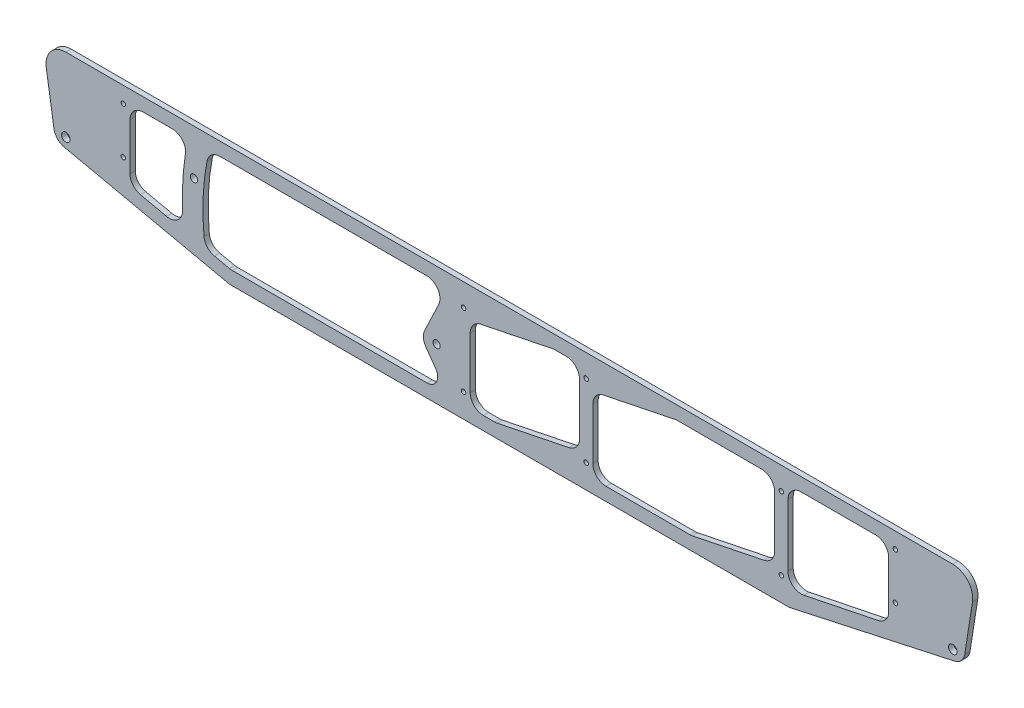
SolidWorks part; units mm, degrees
material "Сплав 2024"
ref_plane "Спереди" through (0, 0, 0) normal (0, 0, 1) x (1, 0, 0)
ref_plane "Сверху" through (0, 0, 0) normal (0, 1, 0) x (1, 0, 0)
ref_plane "Справа" through (0, 0, 0) normal (1, 0, 0) x (0, 0, -1)
sketch "Эскиз1" plane through (0, 0, 0) normal (0, 0, 1) x (1, 0, 0)
  line L0 (-349.8183, 27.6724) -> (-342.9109, -16.3036)
  line L1 (-350, 45) -> (350, 45) construction
  line L2 (-350, 45) -> (-350, -45) construction
  line L3 (-350, -45) -> (350, -45) construction
  line L4 (350, 45) -> (350, -45) construction
  line L5 (-350, 45) -> (350, -45) construction
  line L6 (-350, -45) -> (350, 45) construction
  line L7 (-342.9109, -16.3036) -> (-211.4811, -45)
  line L9 (0, 62.4154) -> (0, -74.3401) construction
  line L10 (-211.4811, -45) -> (211.4811, -45)
  line L12 (-335, 45) -> (335, 45)
  line L15 (342.9109, -16.3036) -> (211.4811, -45)
  line L16 (349.8183, 27.6724) -> (342.9109, -16.3036)
  arc A0 (-335, 45) -> (-349.8183, 27.6724) centre (-335, 30) ccw
  arc A1 (335, 45) -> (349.8183, 27.6724) centre (335, 30) cw
  circle A2 centre (-335, -10.6353) radius 3.25
  circle A3 centre (335, -10.6353) radius 3.25
  point P0 (0, 0)
  point P20 (0, 45)
  point P21 (0, -45)
  dimension "D3" = 30
  dimension "D4" = 6.5
  dimension "D1" = 700
  dimension "D2" = 90
extrude "Бобышка-Вытянуть1" add sketch "Эскиз1" along normal blind 4
sketch "Эскиз2" plane through (0, 0, 4) normal (0, 0, 1) x (1, 0, 0)
  line L0 (0, 49.4785) -> (0, -75.5602) construction
  line L1 (-350, 30) -> (-320, 30) construction
  line L2 (-335, 45) -> (-335, 15) construction
  line L3 (335, 45) -> (335, 15) construction
  line L4 (350, 30) -> (320, 30) construction
  circle A0 centre (-335, 30) radius 15 construction
  arc A1 (-335, 45) -> (-349.8183, 27.6724) centre (-335, 30) ccw construction
  circle A2 centre (-335, 30) radius 10 construction
  circle A4 centre (335, 30) radius 10 construction
  circle A5 centre (335, 30) radius 15 construction
  dimension "D2" = 20
hole_wizard "Отверстие с зазором M51" positions "Эскиз4" profile "Эскиз3" hole size "M5" standard "Ansi Metric"
sketch "Эскиз4" plane through (0, 0, 4) normal (0, 0, 1) x (1, 0, 0)
  line L0 (-335, 45) -> (-335, 15) construction
  line L1 (-350, 30) -> (-320, 30) construction
  line L2 (350, 30) -> (320, 30) construction
  line L3 (335, 45) -> (335, 15) construction
  circle A0 centre (-335, 30) radius 10 construction
  circle A1 centre (335, 30) radius 10 construction
  point P0 (-335, 40)
  point P6 (-345, 30)
  point P10 (-335, 20)
  point P12 (-325, 30)
  point P34 (325, 30)
  point P40 (335, 40)
  point P44 (345, 30)
  point P46 (335, 20)
sketch "Эскиз3" plane through (-335, 40, 4) normal (1, 0, 0) x (0, -1, 0)
  line L0 (0, 0) -> (0, 4)
  line L1 (0, 4) -> (2.75, 4)
  line L2 (2.75, 4) -> (2.75, 0)
  line L5 (2.75, 0) -> (0, 0)
  line L11 (0, -6.35) -> (0, 107.95) construction
  dimension "Диаметр сквозного отверстия" = 5.5
  dimension "Глубина сквозного отверстия" = 4
sketch "Эскиз7" plane through (0, 0, 0) normal (0, 0, -1) x (-1, 0, 0)
  line L0 (211.4811, -45) -> (-211.4811, -45) construction
  arc A0 (349.8183, 27.6724) -> (335, 45) centre (335, 30) ccw construction
  point P0 (55, -6)
  point P4 (238.23, 10.84)
  dimension "D1" = 183.23
  dimension "D2" = 16.84
  dimension "D3" = 280
  dimension "D4" = 39
hole_wizard "Отверстие с зазором M52" positions "Эскиз9" profile "Эскиз8" hole size "M5" standard "Ansi Metric" end condition through all
sketch "Эскиз9" plane through (0, 0, 0) normal (0, 0, -1) x (-1, 0, 0)
  point P0 (55, -6)
  point P3 (238.23, 10.84)
sketch "Эскиз8" plane through (-55, -6, 0) normal (1, 0, 0) x (0, 1, 0)
  line L0 (0, 0) -> (0, 4)
  line L1 (0, 4) -> (2.75, 4)
  line L2 (2.75, 4) -> (2.75, 0)
  line L5 (2.75, 0) -> (0, 0)
  line L11 (0, -6.35) -> (0, 107.95) construction
  dimension "Диаметр сквозного отверстия" = 5.5
  dimension "Глубина сквозного отверстия" = 4
sketch "Эскиз10" plane through (0, 0, 4) normal (0, 0, 1) x (1, 0, 0)
  line L0 (-286.5713, 35) -> (-242.5713, 35)
  line L1 (335, 45) -> (-335, 45) construction
  line L2 (-286.5713, 35) -> (-286.5713, -18.3692)
  line L3 (-286.5713, -18.3692) -> (-245.8185, -27.2672)
  line L4 (0, 45) -> (0, -45) construction
  line L5 (-342.9109, -16.3036) -> (-211.4811, -45) construction
  line L6 (-226.6719, 35) -> (-46.5878, 35)
  line L7 (-210.4021, -35) -> (-46.5878, -35)
  line L8 (-211.4811, -45) -> (211.4811, -45) construction
  line L9 (-210.4021, -35) -> (-229.7525, -30.775)
  line L10 (-46.5878, 35) -> (-64.032, -1.7078)
  line L11 (-46.5878, -35) -> (-63.1395, -11.8093)
  line L12 (286.5713, 35) -> (286.5713, -18.3692)
  line L13 (286.5713, -18.3692) -> (210.4021, -34)
  line L14 (286.5713, 35) -> (210.4021, 35)
  line L15 (210.4021, 35) -> (210.4021, -34)
  line L16 (210.4021, -42) -> (210.4021, 43) construction
  line L17 (200.4021, 35) -> (126.1451, 35)
  line L18 (200.4021, -42) -> (200.4021, 43) construction
  line L19 (-29.5979, -42) -> (-29.5979, 43) construction
  line L20 (-29.5979, 22.0494) -> (-29.5979, -35)
  line L21 (-29.5979, -35) -> (-10.0721, -35)
  line L22 (200.4021, -22.0494) -> (200.4021, 35)
  line L23 (53.0365, 35) -> (53.0365, -22.0494)
  line L24 (63.0365, 22.0494) -> (63.0365, -35)
  line L25 (33.5107, 35) -> (-29.5979, 22.0494)
  line L26 (200.4021, -22.0494) -> (137.2934, -35)
  line L28 (63.0365, -35) -> (137.2934, -35)
  line L29 (126.1451, 35) -> (63.0365, 22.0494)
  line L30 (53.0365, -22.0494) -> (-10.0721, -35)
  line L34 (53.0365, 35) -> (33.5107, 35)
  arc A0 (-64.032, -1.7078) -> (-63.1395, -11.8093) centre (-55, -6) ccw
  arc A2 (-242.5713, 35) -> (-245.8185, -27.2672) centre (-55, -6) ccw
  arc A3 (-226.6719, 35) -> (-229.7525, -30.775) centre (-55, -6) ccw
  dimension "D4" = 384
  dimension "D5" = 353
  dimension "D2" = 20
  dimension "D1" = 10
  dimension "D3" = 10
  dimension "D6" = 10
  dimension "D7" = 10
  dimension "D8" = 10
  dimension "D9" = 44
  dimension "D10" = 10
  dimension "D11" = 57.0494
extrude "Вырез-Вытянуть3" cut sketch "Эскиз10" against normal through all
fillet "Скругление2" radius 10 16 edges at (-46.5878, 35, 2) (-210.4021, -35, 2) (-229.7525, -30.775, 2) (-226.6719, 35, 2) (-242.5713, 35, 2) (-245.8185, -27.2672, 2) (-286.5713, -18.3692, 2) (-286.5713, 35, 2) (-342.9109, -16.3036, 2) (-211.4811, -45, 2) (211.4811, -45, 2) (342.9109, -16.3036, 2) (286.5713, 35, 2) (286.5713, -18.3692, 2) (210.4021, 35, 2) (210.4021, -34, 2)
fillet "Скругление3" radius 10 12 edges at (-29.5979, -35, 2) (200.4021, 35, 2) (53.0365, 35, 2) (200.4021, -22.0494, 2) (137.2934, -35, 2) (33.5107, 35, 2) (-29.5979, 22.0494, 2) (63.0365, -35, 2) (126.1451, 35, 2) (63.0365, 22.0494, 2) (53.0365, -22.0494, 2) (-10.0721, -35, 2)
sketch "Эскиз11" plane through (0, 0, 4) normal (0, 0, 1) x (1, 0, 0)
  line L0 (205.4021, 45) -> (205.4021, -45) construction
  line L1 (335, 45) -> (-335, 45) construction
  line L2 (-210.4021, -45) -> (210.4021, -45) construction
  line L3 (200.4021, -13.8931) -> (200.4021, 25) construction
  line L4 (199.8709, -27) -> (211.9144, -27) construction
  line L5 (202.3145, 28) -> (208.249, 28) construction
  line L6 (-34.5979, 45) -> (-34.5979, -45) construction
  line L7 (-29.5979, 13.8931) -> (-29.5979, -25) construction
  line L8 (-39.6608, -27) -> (-30.9685, -27) construction
  line L9 (-37.6326, 28) -> (-30.9685, 28) construction
  line L10 (291.5713, 36.1496) -> (291.5713, -11.5594) construction
  line L11 (286.5713, -10.2129) -> (286.5713, 25) construction
  line L12 (294.823, -2) -> (288.4097, -2) construction
  line L13 (294.823, 33) -> (288.4097, 33) construction
  line L14 (0, 45) -> (0, 71.0849) construction
  line L15 (-294.823, 33) -> (-288.4097, 33) construction
  line L16 (-294.823, -2) -> (-288.4097, -2) construction
  line L17 (-291.5713, 36.1496) -> (-291.5713, -11.5594) construction
  line L18 (58.0365, 45) -> (58.0365, -45) construction
  line L19 (53.0365, -13.8931) -> (53.0365, 25) construction
  line L20 (53.8048, -27) -> (63.1419, -27) construction
  line L21 (64.656, 28) -> (53.8048, 28) construction
  dimension "D1" = 5
  dimension "D2" = 18
  dimension "D3" = 55
  dimension "D4" = 5
  dimension "D5" = 18
  dimension "D6" = 55
  dimension "D7" = 5
  dimension "D8" = 35
  dimension "D9" = 5
  dimension "D10" = 18
  dimension "D11" = 55
hole_wizard "Отверстие с зазором M31" positions "Эскиз13" profile "Эскиз12" hole size "M3" standard "Ansi Metric" end condition through all
sketch "Эскиз13" plane through (0, 0, 4) normal (0, 0, 1) x (1, 0, 0)
  line L0 (-34.5979, 45) -> (-34.5979, -45) construction
  line L1 (-37.6326, 28) -> (-30.9685, 28) construction
  line L2 (-39.6608, -27) -> (-30.9685, -27) construction
  line L3 (205.4021, 45) -> (205.4021, -45) construction
  line L4 (199.8709, -27) -> (211.9144, -27) construction
  line L5 (202.3145, 28) -> (208.249, 28) construction
  line L6 (291.5713, 36.1496) -> (291.5713, -11.5594) construction
  line L7 (294.823, 33) -> (288.4097, 33) construction
  line L8 (294.823, -2) -> (288.4097, -2) construction
  line L9 (-294.823, -2) -> (-288.4097, -2) construction
  line L10 (-294.823, 33) -> (-288.4097, 33) construction
  line L11 (-291.5713, 36.1496) -> (-291.5713, -11.5594) construction
  line L12 (58.0365, 45) -> (58.0365, -45) construction
  line L13 (64.656, 28) -> (53.8048, 28) construction
  line L14 (53.8048, -27) -> (63.1419, -27) construction
  point P0 (-34.5979, 28)
  point P6 (-34.5979, -27)
  point P10 (205.4021, -27)
  point P16 (205.4021, 28)
  point P22 (291.5713, 33)
  point P28 (291.6163, -2)
  point P32 (-291.6163, -2)
  point P36 (-291.5713, 33)
  point P49 (58.0365, 28)
  point P55 (58.0365, -27)
sketch "Эскиз12" plane through (-34.5979, 28, 4) normal (1, 0, 0) x (0, -1, 0)
  line L0 (0, 0) -> (0, 4)
  line L1 (0, 4) -> (1.7, 4)
  line L2 (1.7, 4) -> (1.7, 0)
  line L5 (1.7, 0) -> (0, 0)
  line L11 (0, -6.35) -> (0, 107.95) construction
  dimension "Диаметр сквозного отверстия" = 3.4
  dimension "Глубина сквозного отверстия" = 4
sketch "Эскиз14" plane through (0, 0, 4) normal (0, 0, 1) x (1, 0, 0)
  line L0 (0, 59.2479) -> (0, -65.4566) construction
fillet "Скругление4" radius 8 1 edges at (-46.5878, -35, 2)
